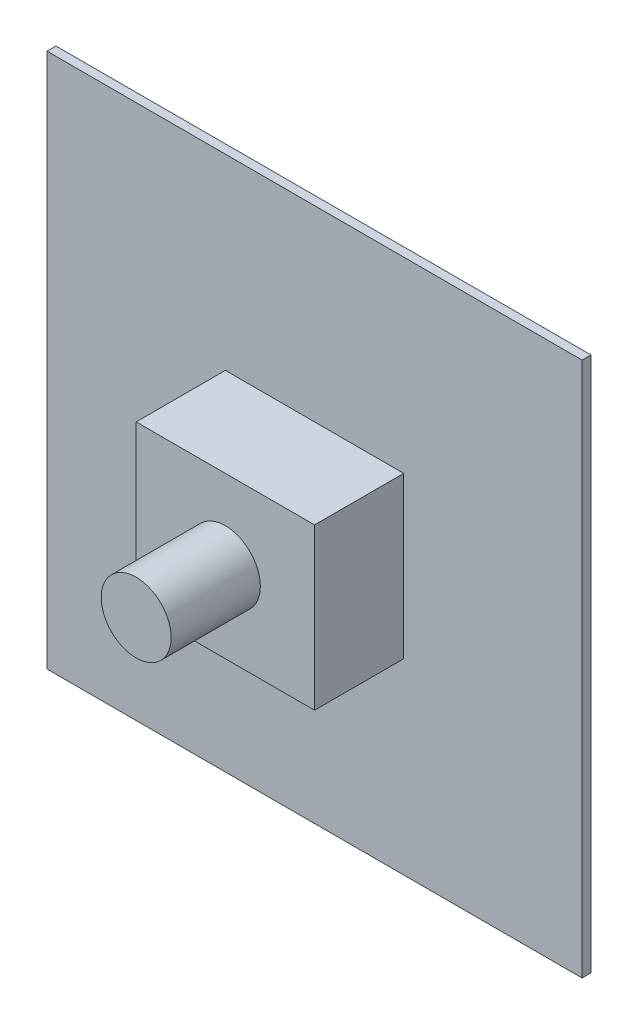
SolidWorks part; units mm, degrees
ref_plane "前基準面" through (0, 0, 0) normal (0, 0, 1) x (1, 0, 0)
ref_plane "上基準面" through (0, 0, 0) normal (0, 1, 0) x (1, 0, 0)
ref_plane "右基準面" through (0, 0, 0) normal (1, 0, 0) x (0, 0, -1)
sketch "草圖1" plane through (0, 0, 0) normal (0, 0, 1) x (1, 0, 0)
  line L1 (-1500, 1500) -> (1500, 1500)
  line L2 (-1500, 1500) -> (-1500, -1500)
  line L3 (-1500, -1500) -> (1500, -1500)
  line L4 (1500, 1500) -> (1500, -1500)
  line L5 (-1500, 1500) -> (1500, -1500) construction
  line L6 (-1500, -1500) -> (1500, 1500) construction
  point P0 (0, 0)
  dimension "D1" = 3000
  dimension "D2" = 3000
extrude "填料-伸長1" add sketch "草圖1" along normal blind 50
sketch "草圖2" plane through (0, 0, 50) normal (0, 0, 1) x (1, 0, 0)
  line L1 (-500, 450) -> (500, 450)
  line L2 (-500, 450) -> (-500, -450)
  line L3 (-500, -450) -> (500, -450)
  line L4 (500, 450) -> (500, -450)
  line L5 (-500, 450) -> (500, -450) construction
  line L6 (-500, -450) -> (500, 450) construction
  point P0 (0, 0)
  dimension "D1" = 1000
  dimension "D2" = 900
extrude "填料-伸長2" add sketch "草圖2" along normal blind 500
sketch "草圖3" plane through (0, 0, 550) normal (0, 0, 1) x (1, 0, 0)
  circle A0 centre (0, 0) radius 196.1311
extrude "填料-伸長3" add sketch "草圖3" along normal blind 500
